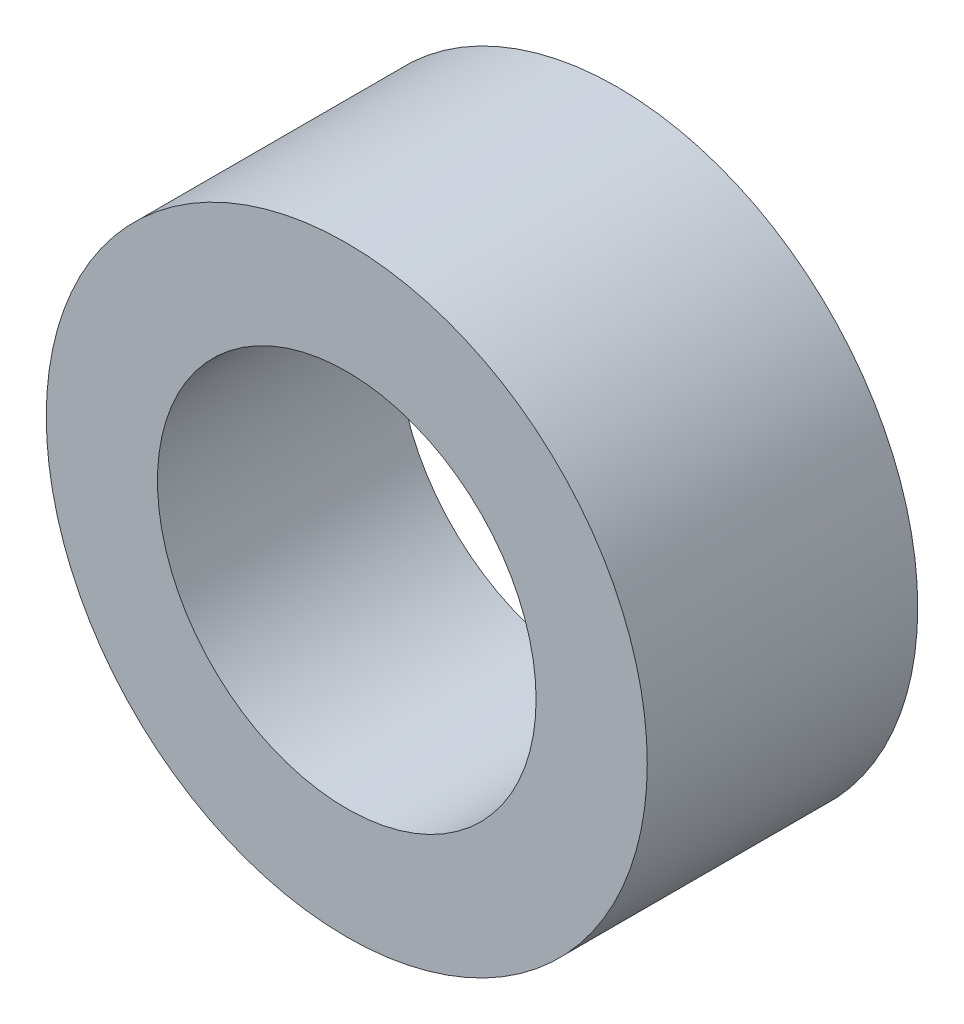
SolidWorks part; units mm, degrees
material "Cast Carbon Steel"
ref_plane "Plane1" through (0, 0, 0) normal (0, 0, 1) x (1, 0, 0)
ref_plane "Plane2" through (0, 0, 0) normal (0, 1, 0) x (1, 0, 0)
ref_plane "Plane3" through (0, 0, 0) normal (1, 0, 0) x (0, 0, -1)
other "Configuration Table"
sketch "Sketch1" plane through (0, 0, 0) normal (0, 0, 1) x (1, 0, 0)
  line L0 (0, 0) -> (0, 17.7062) construction
  line L1 (0, 0) -> (31.5137, 0) construction
  circle A0 centre (0, 0) radius 10
  dimension "D1" = 20
extrude "Extrude1" add sketch "Sketch1" along normal blind 8
sketch "Sketch3" plane through (0, 0, 0) normal (0, 0, -1) x (-1, 0, 0)
  circle A0 centre (0, 0) radius 9
  circle A1 centre (0, 0) radius 10
  circle A2 centre (0, 0) radius 10
  dimension "D1" = 0
  dimension "D2" = 1
extrude "Extrude2" add sketch "Sketch3" along normal blind 1
sketch "Sketch2" plane through (0, 0, 8) normal (0, 0, 1) x (1, 0, 0)
  circle A0 centre (0, 0) radius 6.3
  dimension "D1" = 12.6
extrude "Cut-Extrude1" cut sketch "Sketch2" against normal through all
